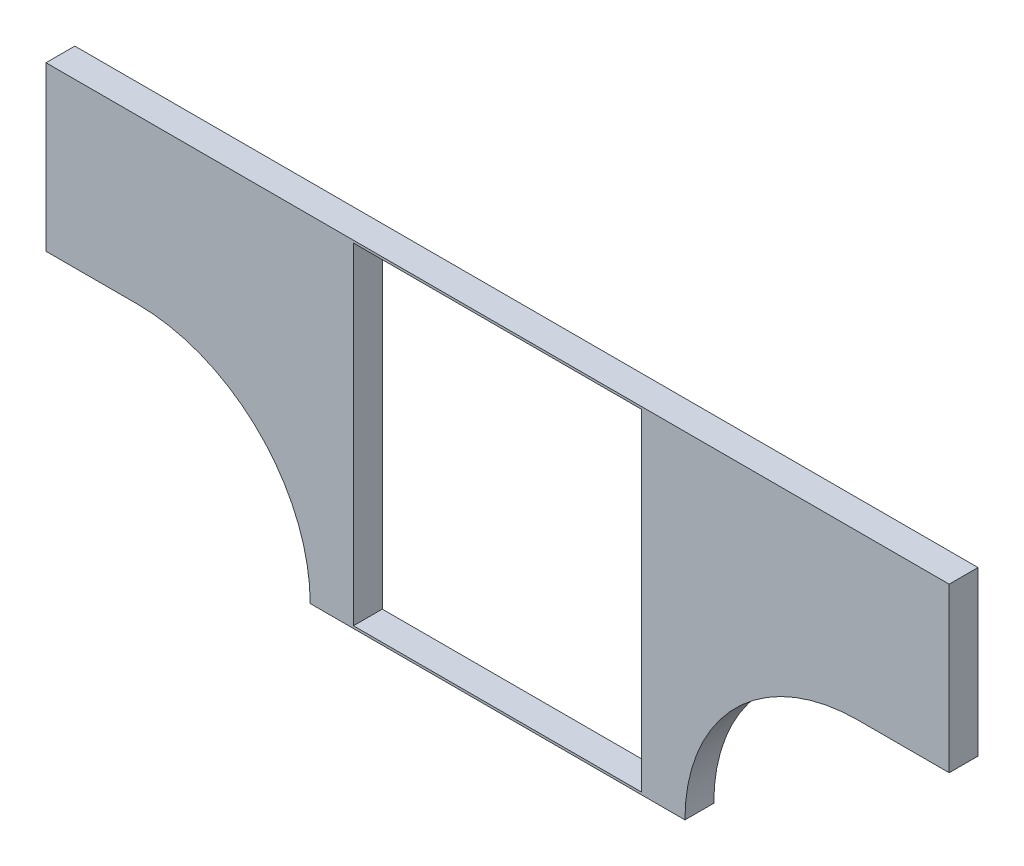
SolidWorks part; units mm, degrees
ref_plane "Front Plane" through (0, 0, 0) normal (0, 0, 1) x (1, 0, 0)
ref_plane "Top Plane" through (0, 0, 0) normal (0, 1, 0) x (1, 0, 0)
ref_plane "Right Plane" through (0, 0, 0) normal (1, 0, 0) x (0, 0, -1)
sketch "Sketch1" plane through (0, 0, 0) normal (0, 0, 1) x (1, 0, 0)
  line L0 (1500, 20) -> (2000, 20)
  line L1 (-2000, -700) -> (2000, -700)
  line L2 (-2000, -700) -> (-2000, 700)
  line L3 (-2000, 700) -> (2000, 700)
  line L4 (2000, -700) -> (2000, 700)
  line L5 (0, 700) -> (0, -700) construction
  line L6 (-1331.477, 0) -> (2000, 0) construction
  line L7 (-1500, 20) -> (-2000, 20)
  line L9 (-2000, 700) -> (-1880, 700)
  line L10 (-2000, 700) -> (-2000, 20)
  line L11 (-2000, 20) -> (-1880, 20)
  line L12 (-1880, 700) -> (-1880, 20)
  line L13 (2000, 700) -> (1880, 700)
  line L14 (2000, 700) -> (2000, 20)
  line L15 (2000, 20) -> (1880, 20)
  line L16 (1880, 700) -> (1880, 20)
  arc A0 (-780, -700) -> (-1500, 20) centre (-1500, -700) ccw
  arc A1 (780, -700) -> (1500, 20) centre (1500, -700) cw
  point P0 (0, 0)
  dimension "D3" = 500
  dimension "D1" = 4000
  dimension "D2" = 1400
  dimension "D4" = 120
  dimension "D5" = 120
extrude "Boss-Extrude1" add sketch "Sketch1" along normal blind 120 contours L1 A1 L0 L4 L3 L2 L7 A0
sketch "Sketch2" plane through (0, 0, 0) normal (0, 0, -1) x (-1, 0, 0)
  line L0 (1880, 700) -> (-1880, 700) construction
  line L1 (-600, 700) -> (600, 700)
  line L2 (-600, 700) -> (-600, -700)
  line L3 (-600, -700) -> (600, -700)
  line L4 (600, 700) -> (600, -700)
  line L5 (780, -700) -> (-780, -700) construction
  line L8 (-1880, 700) -> (-1880, 20) construction
  line L9 (-600, 690) -> (600, 690)
  line L10 (-600, 690) -> (-600, -690)
  line L11 (-600, -690) -> (600, -690)
  line L12 (600, 690) -> (600, -690)
  dimension "D1" = 1200
  dimension "D2" = 1280
  dimension "D3" = 10
  dimension "D4" = 10
extrude "Cut-Extrude1" cut sketch "Sketch2" against normal blind 120 contours L2 L11 L4 L9
